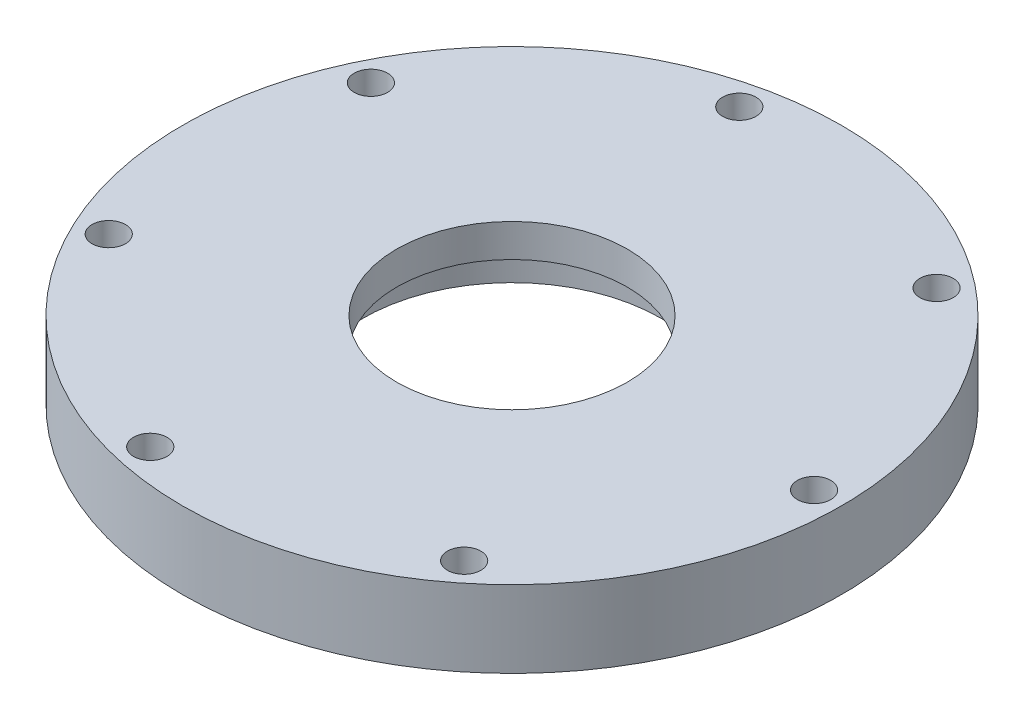
SolidWorks part; units mm, degrees
ref_plane "Alzado" through (0, 0, 0) normal (0, 0, 1) x (1, 0, 0)
ref_plane "Planta" through (0, 0, 0) normal (0, 1, 0) x (1, 0, 0)
ref_plane "Vista lateral" through (0, 0, 0) normal (1, 0, 0) x (0, 0, -1)
sketch "Croquis1" plane through (0, 0, 0) normal (0, 1, 0) x (1, 0, 0)
  circle A0 centre (0, 0) radius 30
  circle A1 centre (0, 0) radius 10.5
  dimension "D1" = 60
  dimension "D2" = 21
extrude "Saliente-Extruir1" add sketch "Croquis1" along normal blind 7
sketch "Croquis2" plane through (0, 0, 0) normal (0, -1, 0) x (1, 0, 0)
  circle A0 centre (0, 0) radius 13.575
  dimension "D1" = 27.15
extrude "Cortar-Extruir1" cut sketch "Croquis2" against normal blind 4
sketch "Croquis3" plane through (0, 7, 0) normal (0, 1, 0) x (1, 0, 0)
  circle A0 centre (27.5, 0) radius 1.52
  circle A1 centre (17.146, -21.5004) radius 1.52
  circle A2 centre (-6.1193, -26.8105) radius 1.52
  circle A3 centre (-24.7766, -11.9318) radius 1.52
  circle A4 centre (-24.7766, 11.9318) radius 1.52
  circle A5 centre (-6.1193, 26.8105) radius 1.52
  circle A6 centre (17.146, 21.5004) radius 1.52
  point P18 (0, 0)
  dimension "D2" = 3.04
  dimension "D1" = 27.5
  dimension "D3" = 7
extrude "Cortar-Extruir2" cut sketch "Croquis3" against normal through all
